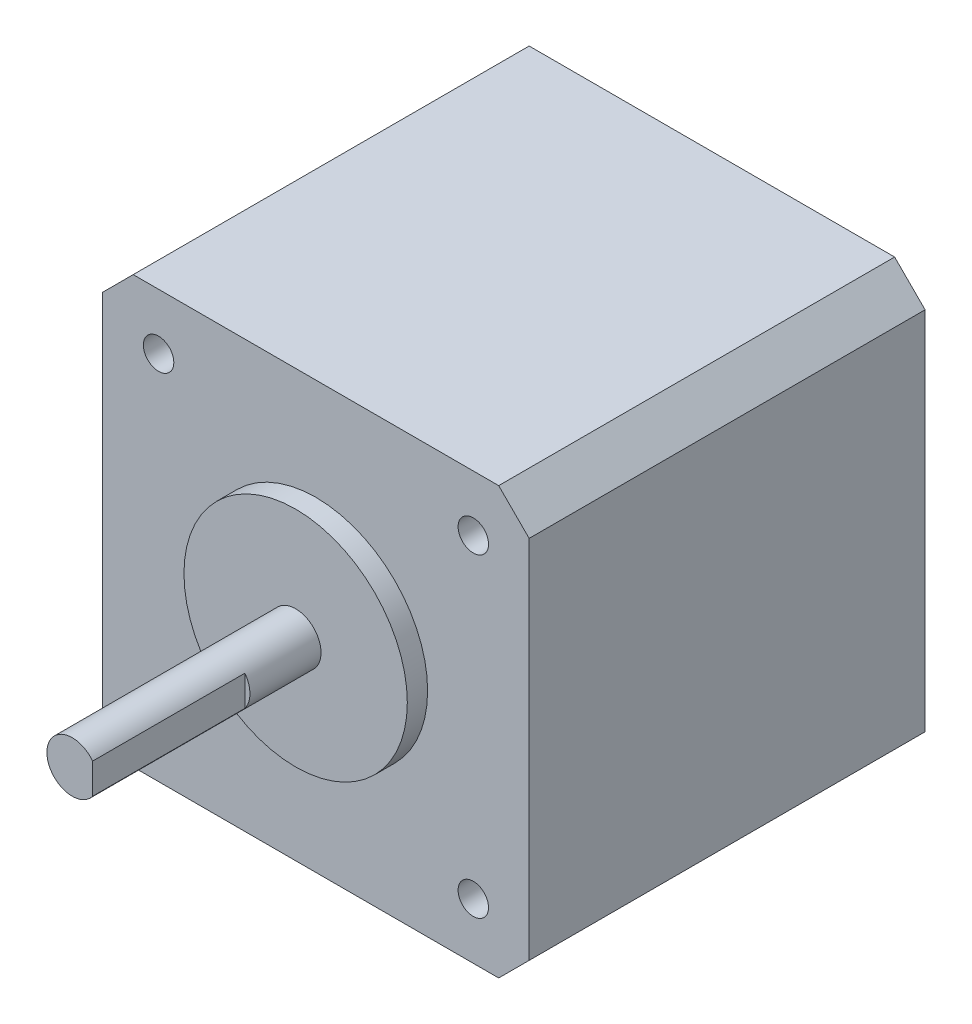
SolidWorks part; units mm, degrees
ref_plane "Front Plane" through (0, 0, 0) normal (0, 0, 1) x (1, 0, 0)
ref_plane "Top Plane" through (0, 0, 0) normal (0, 1, 0) x (1, 0, 0)
ref_plane "Right Plane" through (0, 0, 0) normal (1, 0, 0) x (0, 0, -1)
sketch "Sketch1" plane through (0, 0, 0) normal (0, 0, 1) x (1, 0, 0)
  line L1 (0, 0) -> (42, 0)
  line L2 (0, 0) -> (0, 42)
  line L3 (0, 42) -> (42, 42)
  line L4 (42, 0) -> (42, 42)
  dimension "D1" = 42
  dimension "D2" = 42
extrude "Boss-Extrude1" add sketch "Sketch1" along normal blind 39
sketch "Sketch2" plane through (0, 0, 39) normal (0, 0, 1) x (1, 0, 0)
  line L0 (0, 21) -> (42, 21) construction
  line L1 (0, 42) -> (0, 0) construction
  line L2 (42, 0) -> (42, 42) construction
  line L3 (21, 42) -> (21, 0) construction
  line L4 (42, 42) -> (0, 42) construction
  line L5 (0, 0) -> (42, 0) construction
  circle A0 centre (21, 21) radius 11
  dimension "D1" = 22
extrude "Boss-Extrude2" add sketch "Sketch2" along normal blind 2
sketch "Sketch3" plane through (0, 0, 41) normal (0, 0, 1) x (1, 0, 0)
  line L0 (21, 32) -> (21, 10) construction
  line L2 (32, 21) -> (10, 21) construction
  circle A0 centre (21, 21) radius 11 construction
  circle A1 centre (21, 21) radius 11 construction
  circle A2 centre (21, 21) radius 2.5
  dimension "D1" = 5
extrude "Boss-Extrude3" add sketch "Sketch3" along normal blind 22
chamfer "Chamfer1" distance 3 angle 45 4 edges at (0, 0, 19.5) (0, 42, 19.5) (42, 0, 19.5) (42, 42, 19.5)
sketch "Sketch4" plane through (0, 0, 39) normal (0, 0, 1) x (1, 0, 0)
  line L0 (0, 39) -> (0, 3) construction
  line L1 (39, 42) -> (3, 42) construction
  line L2 (42, 3) -> (42, 39) construction
  line L3 (3, 0) -> (39, 0) construction
  circle A0 centre (5.5, 36.5) radius 1.5
  circle A1 centre (5.5, 5.5) radius 1.5
  circle A2 centre (36.5, 5.5) radius 1.5
  circle A3 centre (36.5, 36.5) radius 1.5
  dimension "D5" = 3
  dimension "D6" = 3
  dimension "D11" = 3
  dimension "D12" = 3
  dimension "D1" = 5.5
  dimension "D2" = 5.5
  dimension "D3" = 5.5
  dimension "D4" = 5.5
  dimension "D7" = 5.5
  dimension "D8" = 5.5
  dimension "D9" = 5.5
  dimension "D10" = 5.5
extrude "Cut-Extrude1" cut sketch "Sketch4" against normal blind 10
sketch "Sketch5" plane through (0, 0, 63) normal (0, 0, 1) x (1, 0, 0)
  line L0 (23, 22.5) -> (23, 19.5)
  circle A0 centre (21, 21) radius 2.5 construction
  circle A1 centre (21, 21) radius 2.5 construction
  point P6 (18.5, 21)
  dimension "D1" = 4.5
extrude "Cut-Extrude2" cut sketch "Sketch5" against normal blind 15 and the other way through all
